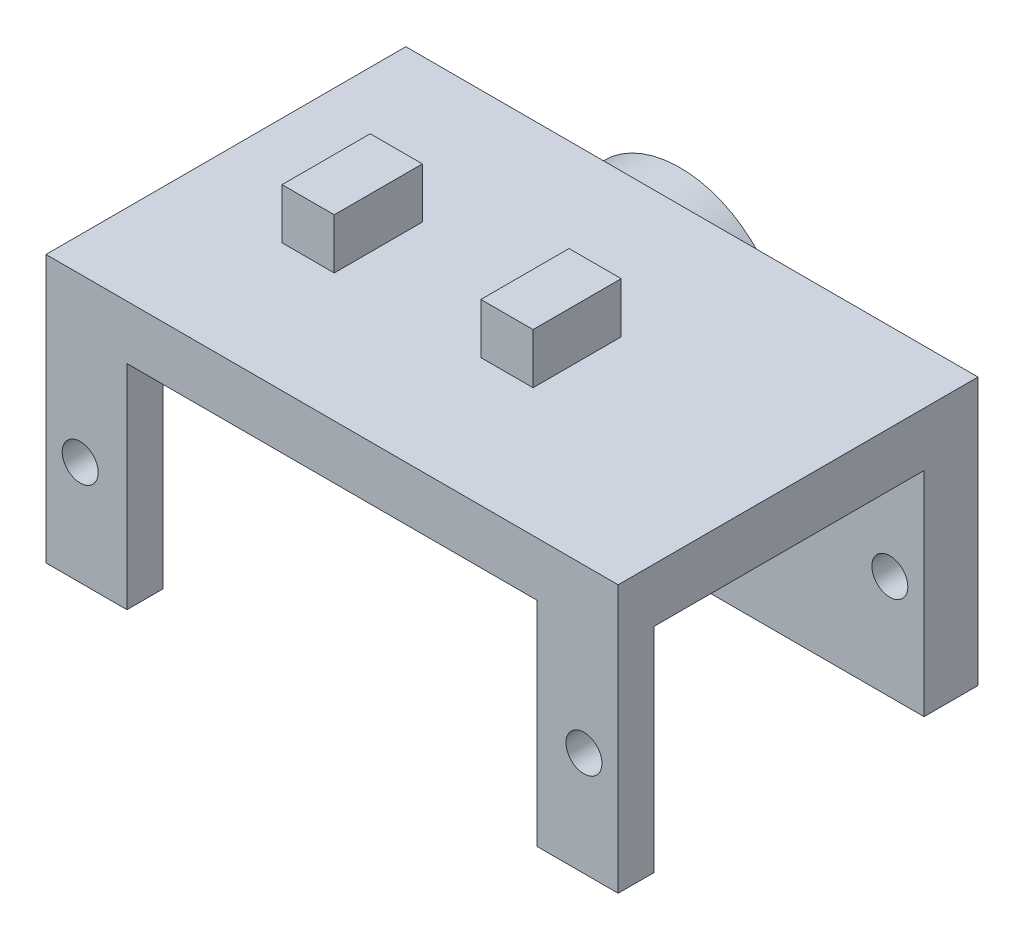
SolidWorks part; units mm, degrees
ref_plane "Front Plane" through (0, 0, 0) normal (0, 0, 1) x (1, 0, 0)
ref_plane "Top Plane" through (0, 0, 0) normal (0, 1, 0) x (1, 0, 0)
ref_plane "Right Plane" through (0, 0, 0) normal (1, 0, 0) x (0, 0, -1)
sketch "Sketch1" plane through (0, 0, 0) normal (0, 0, 1) x (1, 0, 0)
  line L1 (15.9, -6.625) -> (-15.9, -6.625)
  line L2 (15.9, -6.625) -> (15.9, 6.625)
  line L3 (15.9, 6.625) -> (-15.9, 6.625)
  line L4 (-15.9, -6.625) -> (-15.9, 6.625)
  line L5 (15.9, -6.625) -> (-15.9, 6.625) construction
  line L6 (15.9, 6.625) -> (-15.9, -6.625) construction
  point P0 (0, 0)
  dimension "D1" = 31.8
  dimension "D2" = 13.25
extrude "Boss-Extrude3" add sketch "Sketch1" along normal blind 3
sketch "Sketch3" plane through (0, 0, 3) normal (0, 0, 1) x (1, 0, 0)
  line L1 (-15.9, 6.625) -> (15.9, 6.625)
  line L2 (-15.9, 6.625) -> (-15.9, 9.625)
  line L3 (-15.9, 9.625) -> (15.9, 9.625)
  line L4 (15.9, 6.625) -> (15.9, 9.625)
  dimension "D1" = 3
  dimension "D2" = 31.8
extrude "Boss-Extrude4" add sketch "Sketch3" against normal blind 24
sketch "Sketch4" plane through (0, 0, 3) normal (0, 0, 1) x (1, 0, 0)
  line L0 (0, 9.625) -> (0, 6.625)
  line L1 (15.9, 9.625) -> (-15.9, 9.625) construction
  line L2 (-15.9, 9.625) -> (-15.9, -6.625) construction
  line L3 (11.4, -6.625) -> (-11.4, -6.625)
  line L4 (11.4, -6.625) -> (11.4, 6.625)
  line L5 (11.4, 6.625) -> (-11.4, 6.625)
  line L6 (-11.4, -6.625) -> (-11.4, 6.625)
  line L7 (11.4, -6.625) -> (-11.4, 6.625) construction
  line L8 (11.4, 6.625) -> (-11.4, -6.625) construction
  line L9 (-15.9, -6.625) -> (15.9, -6.625) construction
  point P5 (0, 0)
  dimension "D1" = 3
  dimension "D2" = 4.5
  dimension "D3" = 0
extrude "Cut-Extrude3" cut sketch "Sketch4" against normal blind 3 contours L6 L4 L5
sketch "Sketch6" plane through (0, 6.625, 0) normal (0, -1, 0) x (1, 0, 0)
  line L0 (15.9, 3) -> (15.9, -15.4)
  line L1 (15.9, -21) -> (15.9, 0) construction
  line L2 (-15.9, -21) -> (-15.9, 0) construction
  line L3 (15.9, -15.4) -> (-15.9, -15.4)
  line L4 (15.9, -15.4) -> (15.9, -17.4)
  line L5 (15.9, -17.4) -> (-15.9, -17.4)
  line L6 (-15.9, -15.4) -> (-15.9, -17.4)
  line M3 (15.9, -21) -> (15.9, 0)
  line M9 (-15.9, 0) -> (-15.9, -21)
  dimension "D1" = 18.4
  dimension "D2" = 2
extrude "Boss-Extrude5" add sketch "Sketch6" along normal up to surface (13.25 mm away) contours L5 L3 M3 M9 up to face at (-13.65, -6.625, 1.5)
sketch "Sketch7" plane through (-15.9, 0, 0) normal (-1, 0, 0) x (0, 0, 1)
  line L1 (-21, 9.625) -> (-17.4, 9.625)
  line L2 (-21, 9.625) -> (-21, 6.625)
  line L3 (-21, 6.625) -> (-17.4, 6.625)
  line L4 (-17.4, 9.625) -> (-17.4, 6.625)
extrude "Cut-Extrude4" cut sketch "Sketch7" against normal through all
sketch "Sketch8" plane through (15.9, 0, 0) normal (1, 0, 0) x (0, 0, -1)
  line L1 (15.4, -6.625) -> (17.4, -6.625)
  line L2 (15.4, -6.625) -> (15.4, -7.875)
  line L3 (15.4, -7.875) -> (17.4, -7.875)
  line L4 (17.4, -6.625) -> (17.4, -7.875)
  dimension "D1" = 1.25
extrude "Boss-Extrude6" add sketch "Sketch8" against normal up to surface (31.8 mm away) up to face at (-15.9, 0.75, -7.45)
sketch "Sketch10" plane through (15.9, 0, 0) normal (1, 0, 0) x (0, 0, -1)
  line L1 (17.4, 9.625) -> (15.4, 9.625)
  line L2 (17.4, 9.625) -> (17.4, -7.875)
  line L3 (17.4, -7.875) -> (15.4, -7.875)
  line L4 (15.4, 9.625) -> (15.4, -7.875)
extrude "Cut-Extrude6" cut sketch "Sketch10" against normal through all
sketch "Sketch11" plane through (15.9, 0, 0) normal (1, 0, 0) x (0, 0, -1)
  line L1 (-3, -6.625) -> (0, -6.625)
  line L2 (-3, -6.625) -> (-3, -7.875)
  line L3 (-3, -7.875) -> (0, -7.875)
  line L4 (0, -6.625) -> (0, -7.875)
  dimension "D1" = 1.25
extrude "Boss-Extrude7" add sketch "Sketch11" against normal up to surface (27.3 mm away)
ref_plane "Plane7" through (0, 0, 0) normal (1, 0, 0) x (0, 0, -1)
mirror "Mirror2" about plane through (0, 0, 0) normal (1, 0, 0) of "Boss-Extrude7"
sketch "Sketch12" plane through (0, 0, 3) normal (0, 0, 1) x (1, 0, 0)
  line L0 (-15.9, -7.875) -> (15.9, -7.875) construction
  line L1 (-11.4, -6.625) -> (11.4, -6.625)
  line L2 (-11.4, -6.625) -> (-11.4, -7.875)
  line L3 (-11.4, -7.875) -> (11.4, -7.875)
  line L4 (11.4, -6.625) -> (11.4, -7.875)
extrude "Cut-Extrude7" cut sketch "Sketch12" against normal blind 4
sketch "Sketch15" plane through (0, 9.625, 0) normal (0, 1, 0) x (1, 0, 0)
  line L0 (15.9, 15.4) -> (15.9, -3) construction
  line L1 (-15.9, 15.4) -> (15.9, 15.4)
  line L2 (-15.9, 15.4) -> (-15.9, 18.4)
  line L3 (-15.9, 18.4) -> (15.9, 18.4)
  line L4 (15.9, 15.4) -> (15.9, 18.4)
  dimension "D1" = 3
extrude "Boss-Extrude9" add sketch "Sketch15" against normal up to surface (17.5 mm away) up to face at (13.65, -7.875, 1.5)
sketch "Sketch19" plane through (0, 0, 3) normal (0, 0, 1) x (1, 0, 0)
  line L0 (-15.9, 9.625) -> (15.9, 9.625)
  line L1 (15.9, 9.625) -> (15.9, -7.875)
  line L2 (15.9, -7.875) -> (11.4, -7.875)
  line L3 (11.4, -7.875) -> (11.4, 6.625)
  line L4 (11.4, 6.625) -> (-11.4, 6.625)
  line L5 (-11.4, 6.625) -> (-11.4, -7.875)
  line L6 (-11.4, -7.875) -> (-15.9, -7.875)
  line L7 (-15.9, -7.875) -> (-15.9, 9.625)
extrude "Boss-Extrude12" add sketch "Sketch19" against normal blind 5
sketch "Sketch20" plane through (-15.9, 0, 0) normal (-1, 0, 0) x (0, 0, 1)
  line L0 (-2, -7.875) -> (3, -7.875) construction
  line L1 (-15.4, 6.625) -> (-0.4, 6.625)
  line L2 (-15.4, 6.625) -> (-15.4, -7.875)
  line L3 (-15.4, -7.875) -> (-0.4, -7.875)
  line L4 (-0.4, 6.625) -> (-0.4, -7.875)
  line L5 (-18.4, 9.625) -> (3, 9.625) construction
  line L6 (1.6, 9.625) -> (6.8306, 9.625)
  line L7 (1.6, 9.625) -> (1.6, -7.875)
  line L8 (1.6, -7.875) -> (6.8306, -7.875)
  line L9 (6.8306, 9.625) -> (6.8306, -7.875)
  dimension "D1" = 15
  dimension "D2" = 17
extrude "Cut-Extrude9" cut sketch "Sketch20" against normal blind 100
sketch "Sketch22" plane through (0, 0, 1.6) normal (0, 0, 1) x (1, 0, 0)
  line L0 (15.9, 9.625) -> (15.9, -7.875) construction
  line L1 (-15.9, -7.875) -> (15.9, -7.875)
  line L2 (-15.9, -7.875) -> (-15.9, -5.225)
  line L3 (-15.9, -5.225) -> (15.9, -5.225)
  line L4 (15.9, -7.875) -> (15.9, -5.225)
  line L6 (15.9, 6.625) -> (-15.9, 6.625) construction
  line L7 (0, -1.1) -> (0, 1.1) construction
  circle A0 centre (-14, 0.575) radius 1
  circle A1 centre (14, 0.575) radius 1
  dimension "D2" = 14
  dimension "D4" = 2
  dimension "D1" = 11.85
  dimension "D3" = 5.8
extrude "Cut-Extrude11" cut sketch "Sketch22" against normal blind 20
sketch "Sketch24" plane through (0, 0, -18.4) normal (0, 0, -1) x (-1, 0, 0)
  line L0 (-15.9, -5.225) -> (15.9, -5.225) construction
  line L1 (11.4, 6.625) -> (11.4, -5.225) construction
  circle A0 centre (5.47, 0.7) radius 5.925
  dimension "D1" = 5.925
  dimension "D2" = 11.85
  dimension "D3" = 5.93
extrude "Boss-Extrude13" add sketch "Sketch24" along normal blind 4.8
sketch "Sketch25" plane through (0, 0, -23.2) normal (0, 0, -1) x (-1, 0, 0)
  circle A0 centre (5.47, 0.7) radius 2.5
  dimension "D1" = 5
extrude "Boss-Extrude14" add sketch "Sketch25" along normal blind 2
sketch "Sketch26" plane through (0, 9.625, 0) normal (0, 1, 0) x (1, 0, 0)
  line L0 (15.9, 18.4) -> (-15.9, 18.4) construction
  line L1 (-9.9, 10.42) -> (-7, 10.42)
  line L2 (-9.9, 10.42) -> (-9.9, 5.52)
  line L3 (-9.9, 5.52) -> (-7, 5.52)
  line L4 (-7, 10.42) -> (-7, 5.52)
  line L5 (-9.9, 10.42) -> (-7, 5.52) construction
  line L6 (-9.9, 5.52) -> (-7, 10.42) construction
  line L7 (-15.9, 18.4) -> (-15.9, -1.6) construction
  line L9 (1.15, 5.52) -> (4.05, 5.52)
  line L10 (1.15, 5.52) -> (1.15, 10.42)
  line L11 (1.15, 10.42) -> (4.05, 10.42)
  line L12 (4.05, 5.52) -> (4.05, 10.42)
  line L13 (1.15, 5.52) -> (4.05, 10.42) construction
  line L14 (1.15, 10.42) -> (4.05, 5.52) construction
  point P0 (-8.45, 7.97)
  point P9 (2.6, 7.97)
  dimension "D1" = 10.43
  dimension "D2" = 2.9
  dimension "D3" = 4.9
  dimension "D4" = 6
  dimension "D5" = 4.9
  dimension "D6" = 2.9
  dimension "D7" = 12.5
  dimension "D8" = 10.43
extrude "Boss-Extrude15" add sketch "Sketch26" along normal blind 2.8
